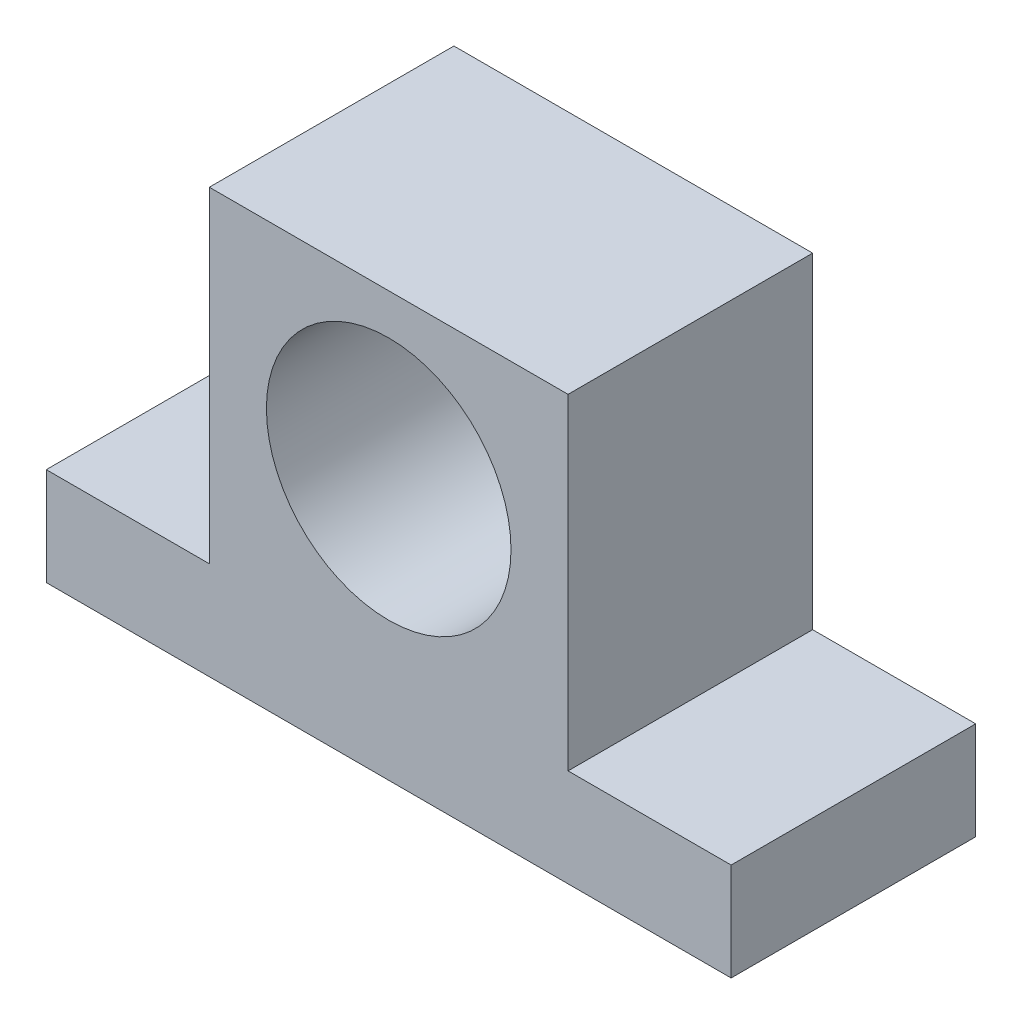
SolidWorks part; units mm, degrees
ref_plane "Plan de face" through (0, 0, 0) normal (0, 0, 1) x (1, 0, 0)
ref_plane "Plan de dessus" through (0, 0, 0) normal (0, 1, 0) x (1, 0, 0)
ref_plane "Plan de droite" through (0, 0, 0) normal (1, 0, 0) x (0, 0, -1)
sketch "Sketch1" plane through (0, 0, 0) normal (0, 0, 1) x (1, 0, 0)
  line L0 (11, -10) -> (21, -10)
  line L2 (11, -10) -> (11, 10)
  line L3 (11, 10) -> (-11, 10)
  line L4 (-11, -10) -> (-11, 10)
  line L5 (11, -10) -> (-11, 10) construction
  line L6 (11, 10) -> (-11, -10) construction
  line L7 (-21, -10) -> (-11, -10)
  line L8 (-21, -10) -> (-21, -16)
  line L9 (-21, -16) -> (21, -16)
  line L10 (21, -10) -> (21, -16)
  circle A0 centre (0, 0) radius 7.5
  dimension "D1" = 15
  dimension "D2" = 22
  dimension "D3" = 20
  dimension "D4" = 10
  dimension "D5" = 10
  dimension "D6" = 16
extrude "Boss-Extrude1" add sketch "Sketch1" along normal blind 15
